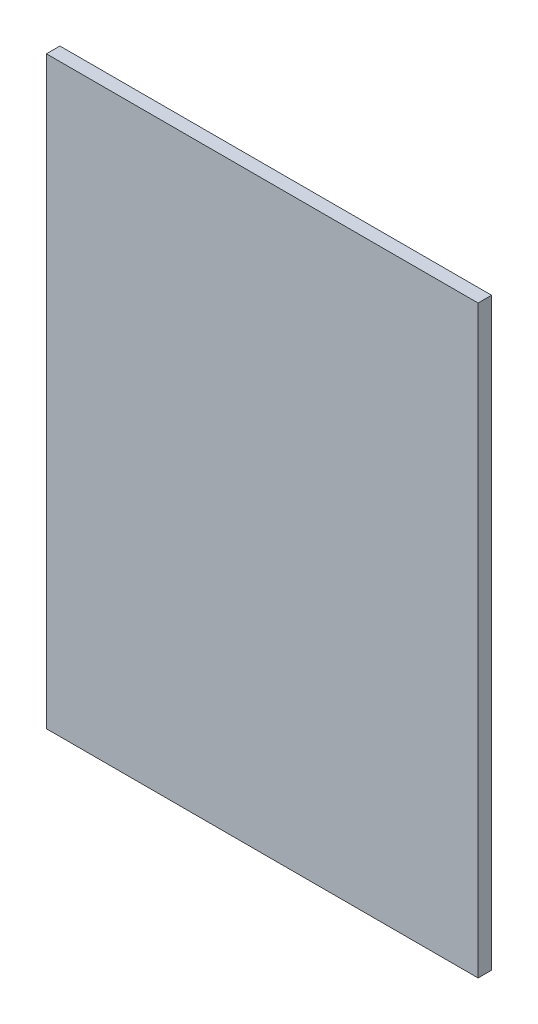
SolidWorks part; units mm, degrees
material "1060 Alloy"
ref_plane "Front Plane" through (0, 0, 0) normal (0, 0, 1) x (1, 0, 0)
ref_plane "Top Plane" through (0, 0, 0) normal (0, 1, 0) x (1, 0, 0)
ref_plane "Right Plane" through (0, 0, 0) normal (1, 0, 0) x (0, 0, -1)
sketch "Sketch1" plane through (0, 0, 0) normal (0, 0, 1) x (1, 0, 0)
  line L1 (-29.4866, 51.6858) -> (66.5134, 51.6858)
  line L2 (-29.4866, 51.6858) -> (-29.4866, -78.3142)
  line L3 (-29.4866, -78.3142) -> (66.5134, -78.3142)
  line L4 (66.5134, 51.6858) -> (66.5134, -78.3142)
  dimension "D1" = 130
  dimension "D2" = 96
extrude "Boss-Extrude1" add sketch "Sketch1" along normal blind 3
